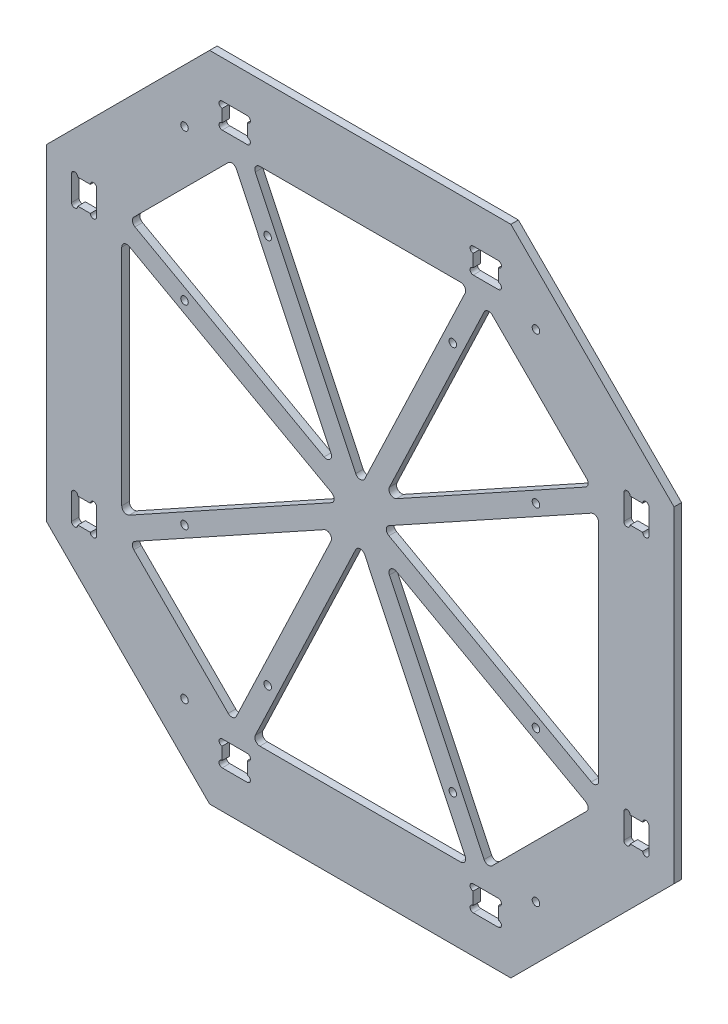
SolidWorks part; units mm, degrees
material "Thornel Mat VMA"
ref_plane "前视基准面" through (0, 0, 0) normal (0, 0, 1) x (1, 0, 0)
ref_plane "上视基准面" through (0, 0, 0) normal (0, 1, 0) x (1, 0, 0)
ref_plane "右视基准面" through (0, 0, 0) normal (1, 0, 0) x (0, 0, -1)
sketch "草图1" plane through (0, 0, 0) normal (0, 0, 1) x (1, 0, 0)
  line L1 (-125, -130) -> (125, -130)
  line L2 (-125, -130) -> (-125, 130)
  line L3 (-125, 130) -> (125, 130)
  line L4 (125, -130) -> (125, 130)
  line L5 (0, 130) -> (0, -130) construction
  line L6 (-125, 0) -> (125, 0) construction
  point P0 (0, 0)
  dimension "D1" = 250
  dimension "D2" = 260
extrude "凸台-拉伸1" add sketch "草图1" along normal mid plane 3
sketch "草图2" plane through (0, 0, -1.5) normal (0, 0, -1) x (-1, 0, 0)
  line L0 (0, 0) -> (125, 0) construction
  line L1 (125, 130) -> (125, -130) construction
  line L2 (55, -105) -> (55, -115)
  line L3 (45, -105) -> (55, -105)
  line L4 (-55, 105) -> (-45, 105)
  line L5 (-45, 105) -> (-45, 115)
  line L6 (-45, 115) -> (-55, 115)
  line L7 (-55, 115) -> (-55, 105)
  line L8 (-55, 105) -> (-45, 105)
  line L9 (-45, 105) -> (-45, 115)
  line L10 (-45, 115) -> (-55, 115)
  line L11 (-55, 115) -> (-55, 105)
  line L12 (55, 115) -> (45, 115)
  line L13 (45, 115) -> (45, 105)
  line L14 (45, 105) -> (55, 105)
  line L15 (55, 105) -> (55, 115)
  line L16 (55, 115) -> (45, 115)
  line L17 (45, 115) -> (45, 105)
  line L18 (45, 105) -> (55, 105)
  line L19 (55, 105) -> (55, 115)
  line L20 (105, 60) -> (105, 50)
  line L21 (105, 50) -> (115, 50)
  line L22 (115, 50) -> (115, 60)
  line L23 (115, 60) -> (105, 60)
  line L24 (105, 60) -> (105, 50)
  line L25 (105, 50) -> (115, 50)
  line L26 (115, 50) -> (115, 60)
  line L27 (115, 60) -> (105, 60)
  line L28 (115, -60) -> (115, -50)
  line L29 (115, -50) -> (105, -50)
  line L30 (105, -50) -> (105, -60)
  line L31 (105, -60) -> (115, -60)
  line L32 (115, -60) -> (115, -50)
  line L33 (115, -50) -> (105, -50)
  line L34 (105, -50) -> (105, -60)
  line L35 (105, -60) -> (115, -60)
  line L36 (45, -115) -> (45, -105)
  line L37 (55, -115) -> (45, -115)
  line L38 (-55, -115) -> (-55, -105)
  line L39 (-45, -115) -> (-55, -115)
  line L40 (-45, -105) -> (-45, -115)
  line L41 (-55, -105) -> (-45, -105)
  line L42 (0, 0) -> (0, 130) construction
  line L43 (-125, 130) -> (125, 130) construction
  line L44 (-115, 60) -> (-105, 60)
  line L45 (-115, 50) -> (-115, 60)
  line L46 (-105, 50) -> (-115, 50)
  line L47 (-105, 60) -> (-105, 50)
  line L48 (-105, -60) -> (-115, -60)
  line L49 (-105, -50) -> (-105, -60)
  line L50 (-115, -50) -> (-105, -50)
  line L51 (-115, -60) -> (-115, -50)
  dimension "D1" = 0
  dimension "D2" = 0
  dimension "D3" = 0
  dimension "D4" = 0
extrude "切除-拉伸1" cut sketch "草图2" against normal mid plane 10
sketch "草图3" plane through (0, 0, -1.5) normal (0, 0, -1) x (-1, 0, 0)
  line L0 (-55, 115) -> (-55, 105) construction
  line L1 (-45, 105) -> (-45, 115) construction
  line L2 (0, 0) -> (0, 130) construction
  line L3 (-125, 130) -> (125, 130) construction
  circle A0 centre (-55, 113.75) radius 1.25
  circle A1 centre (-55, 106.25) radius 1.25
  circle A2 centre (-45, 106.25) radius 1.25
  circle A3 centre (-45, 113.75) radius 1.25
  circle A4 centre (45, 113.75) radius 1.25
  circle A5 centre (45, 106.25) radius 1.25
  circle A6 centre (55, 106.25) radius 1.25
  circle A7 centre (55, 113.75) radius 1.25
  dimension "D1" = 2.5
extrude "切除-拉伸2" cut sketch "草图3" against normal mid plane 10
sketch "草图4" plane through (0, 0, -1.5) normal (0, 0, -1) x (-1, 0, 0)
  line L0 (115, 60) -> (105, 60) construction
  line L1 (105, 50) -> (115, 50) construction
  line L2 (105, 60) -> (105, 50) construction
  line L3 (0, 0) -> (125, 0) construction
  line L4 (125, 130) -> (125, -130) construction
  circle A0 centre (106.25, 60) radius 1.25
  circle A1 centre (113.75, 60) radius 1.25
  circle A2 centre (106.25, 50) radius 1.25
  circle A3 centre (113.75, 50) radius 1.25
  circle A4 centre (113.75, -50) radius 1.25
  circle A5 centre (106.25, -50) radius 1.25
  circle A6 centre (113.75, -60) radius 1.25
  circle A7 centre (106.25, -60) radius 1.25
  dimension "D1" = 2.5
extrude "切除-拉伸3" cut sketch "草图4" against normal mid plane 10
mirror "镜向1" about plane through (0, 0, 0) normal (1, 0, 0) of "切除-拉伸3"
mirror "镜向2" about plane through (0, 0, 0) normal (0, 1, 0) of "切除-拉伸2"
sketch "草图5" plane through (0, 0, -1.5) normal (0, 0, -1) x (-1, 0, 0)
  line L0 (-60, 130) -> (-125, 65)
  line L1 (-125, 130) -> (125, 130) construction
  line L2 (-125, -130) -> (-125, 130) construction
  line L3 (-55, 112.5) -> (-55, 107.5) construction
  line L4 (-107.5, 60) -> (-112.5, 60) construction
  line L5 (0, 0) -> (125, 0) construction
  line L6 (125, 130) -> (125, -130) construction
  line L7 (-125, 65) -> (-125, 130)
  line L8 (-125, 130) -> (-60, 130)
  line L9 (-125, -130) -> (-60, -130)
  line L10 (-125, -65) -> (-125, -130)
  line L11 (-60, -130) -> (-125, -65)
  dimension "D1" = 5
  dimension "D2" = 5
extrude "切除-拉伸4" cut sketch "草图5" against normal mid plane 10
mirror "镜向3" about plane through (0, 0, 0) normal (1, 0, 0) of "切除-拉伸4"
sketch "草图6" plane through (0, 0, -1.5) normal (0, 0, -1) x (-1, 0, 0)
  line L16 (95, -52.5736) -> (95, 52.5736)
  line L17 (95, 52.5736) -> (47.5736, 100)
  line L18 (47.5736, 100) -> (-47.5736, 100)
  line L19 (-47.5736, 100) -> (-95, 52.5736)
  line L20 (-95, 52.5736) -> (-95, -52.5736)
  line L21 (-95, -52.5736) -> (-47.5736, -100)
  line L22 (-47.5736, -100) -> (47.5736, -100)
  line L23 (47.5736, -100) -> (95, -52.5736)
  line L24 (95, -52.5736) -> (95, 52.5736)
  line L25 (95, 52.5736) -> (47.5736, 100)
  line L26 (47.5736, 100) -> (-47.5736, 100)
  line L27 (-47.5736, 100) -> (-95, 52.5736)
  line L28 (-95, 52.5736) -> (-95, -52.5736)
  line L29 (-95, -52.5736) -> (-47.5736, -100)
  line L30 (-47.5736, -100) -> (47.5736, -100)
  line L31 (47.5736, -100) -> (95, -52.5736)
  dimension "D1" = 30
extrude "切除-拉伸5" cut sketch "草图6" against normal mid plane 10
sketch "草图7" plane through (0, 0, -1.5) normal (0, 0, -1) x (-1, 0, 0)
  line L0 (-47.5736, 100) -> (47.5736, -100) construction
  line L1 (47.5736, 100) -> (-47.5736, -100) construction
  line L2 (-95, 52.5736) -> (0, 0) construction
  line L3 (-95, -52.5736) -> (95, 52.5736) construction
  line L4 (-51.1857, 98.2816) -> (-8.9647, 9.5328)
  line L5 (43.9615, 101.7184) -> (0, 9.311)
  line L6 (-96.9368, 49.0738) -> (-8.261, 0)
  line L7 (-93.0632, -56.0734) -> (-8.9647, -9.5328)
  line L8 (-43.9615, 101.7184) -> (0, 9.311)
  line L9 (51.1857, 98.2816) -> (8.9647, 9.5328)
  line L10 (-93.0632, 56.0734) -> (-8.9647, 9.5328)
  line L11 (-96.9368, -49.0738) -> (-8.261, 0)
  line L12 (-51.1857, 98.2816) -> (-43.9615, 101.7184)
  line L13 (43.9615, -101.7184) -> (51.1857, -98.2816)
  line L14 (43.9615, 101.7184) -> (51.1857, 98.2816)
  line L15 (-51.1857, -98.2816) -> (-43.9615, -101.7184)
  line L16 (-96.9368, 49.0738) -> (-93.0632, 56.0734)
  line L17 (93.0632, -56.0734) -> (96.9368, -49.0738)
  line L18 (-93.0632, -56.0734) -> (-96.9368, -49.0738)
  line L19 (96.9368, 49.0738) -> (93.0632, 56.0734)
  line L21 (-93.0632, -56.0734) -> (96.9368, 49.0738) construction
  line L22 (-8.9647, -9.5328) -> (-51.1857, -98.2816)
  line L23 (43.9615, 101.7184) -> (-51.1857, -98.2816) construction
  line L24 (0, -9.311) -> (43.9615, -101.7184)
  line L25 (-51.1857, 98.2816) -> (43.9615, -101.7184) construction
  line L27 (-96.9368, 49.0738) -> (93.0632, -56.0734) construction
  line L29 (-96.9368, -49.0738) -> (93.0632, 56.0734) construction
  line L32 (-93.0632, 56.0734) -> (96.9368, -49.0738) construction
  line L35 (-43.9615, 101.7184) -> (51.1857, -98.2816) construction
  line L36 (8.9647, 9.5328) -> (93.0632, 56.0734)
  line L38 (51.1857, 98.2816) -> (-43.9615, -101.7184) construction
  line L39 (8.261, 0) -> (96.9368, -49.0738)
  line L41 (8.9647, -9.5328) -> (51.1857, -98.2816)
  line L42 (0, 0) -> (95, -52.5736) construction
  line L43 (-95, 52.5736) -> (95, -52.5736) construction
  line L45 (8.261, 0) -> (96.9368, 49.0738)
  line L46 (0, -9.311) -> (-43.9615, -101.7184)
  line L47 (8.9647, -9.5328) -> (93.0632, -56.0734)
  dimension "D1" = 4
  dimension "D2" = 4
extrude "凸台-拉伸2" add sketch "草图7" against normal up to surface (3 mm away) up to face at (0, 0, 1.5)
sketch "草图8" [suppressed] plane through (0, 0, 1.5) normal (0, 0, 1) x (1, 0, 0)
  line L0 (55, 105) -> (45, 105) construction
  line L1 (-105, -105) -> (105, -105)
  line L2 (-105, -105) -> (-105, 105)
  line L3 (-105, 105) -> (105, 105)
  line L4 (105, -105) -> (105, 105)
  line L5 (0, 105) -> (0, -105) construction
  line L6 (-105, 0) -> (105, 0) construction
  line L7 (105, 50) -> (105, 60) construction
  point P0 (0, 0)
extrude "切除-拉伸6" [suppressed] cut sketch "草图8" against normal blind 10
sketch "草图9" plane through (0, 0, -1.5) normal (0, 0, -1) x (-1, 0, 0)
  line L4 (85, 295) -> (55, 295)
  line L5 (55, 295) -> (55, -295)
  line L6 (55, -295) -> (85, -295)
  line L7 (85, -295) -> (85, 295)
  line L8 (85, 295) -> (55, 295) construction
  line L9 (55, 295) -> (55, -295) construction
  line L10 (55, -295) -> (85, -295) construction
  line L11 (85, -295) -> (85, 295) construction
  line L60 (55, 30.4373) -> (85, 47.0395) construction
  line L61 (8.261, 0) -> (95, 48.0019) construction
  line L63 (92.057, 55.5166) -> (8.9647, 9.5328) construction
  line L64 (70, 38.7384) -> (70, 98.7384) construction
  line L65 (0, 0) -> (125, 0) construction
  line L66 (125, 65) -> (125, -65) construction
  line L67 (70, -38.7384) -> (70, -98.7384) construction
  line L68 (55, -30.4373) -> (85, -47.0395) construction
  circle A0 centre (70, 38.7384) radius 1.5
  circle A1 centre (70, 98.7384) radius 1.5
  circle A2 centre (70, -98.7384) radius 1.5
  circle A3 centre (70, -38.7384) radius 1.5
  dimension "D3" = 3
  dimension "D2" = 4
  dimension "D4" = 60
  dimension "D1" = 0
extrude "切除-拉伸7" cut sketch "草图9" against normal blind 10
mirror "镜向4" about plane through (0, 0, 0) normal (1, 0, 0) of "切除-拉伸7"
fillet "圆角1" radius 2 24 edges at (8.261, 0, 0) (95, -48.0019, 0) (95, 48.0019, 0) (8.9647, 9.5328, 0) (92.057, 55.5166, 0) (50.5752, 96.9984, 0) (0, 9.311, 0) (43.144, 100, 0) (-43.144, 100, 0) (-8.9647, 9.5328, 0) (-50.5752, 96.9984, 0) (-92.057, 55.5166, 0) (-8.261, 0, 0) (-95, 48.0019, 0) (-95, -48.0019, 0) (-8.9647, -9.5328, 0) (-92.057, -55.5166, 0) (-50.5752, -96.9984, 0) (0, -9.311, 0) (-43.144, -100, 0) (43.144, -100, 0) (8.9647, -9.5328, 0) (92.057, -55.5166, 0) (50.5752, -96.9984, 0)
sketch "草图10" plane through (0, 0, -1.5) normal (0, 0, -1) x (-1, 0, 0)
  line L0 (-41.7838, -97.1408) -> (-49.0079, -93.704) construction
  line L1 (-36.8695, -77.5) -> (36.8695, -77.5) construction
  line L2 (-36.8695, -77.5) -> (-36.8695, 77.5) construction
  line L3 (-36.8695, 77.5) -> (36.8695, 77.5) construction
  line L4 (36.8695, -77.5) -> (36.8695, 77.5) construction
  line L5 (0, 77.5) -> (0, -77.5) construction
  line L6 (-36.8695, 0) -> (36.8695, 0) construction
  line L7 (-41.7838, -97.1408) -> (-1.806, -13.1073) construction
  line L8 (-11.641, -15.1583) -> (-49.3582, -94.4402) construction
  line L9 (-45.3959, -95.4224) -> (44.5639, 93.6735) construction
  line L10 (11.641, 15.1583) -> (49.3582, 94.4402) construction
  circle A0 centre (36.8695, 77.5) radius 1.5
  circle A1 centre (-36.8695, 77.5) radius 1.5
  circle A2 centre (-36.8695, -77.5) radius 1.5
  circle A3 centre (36.8695, -77.5) radius 1.5
  point P0 (0, 0)
  dimension "D2" = 3
  dimension "D1" = 155
extrude "切除-拉伸8" cut sketch "草图10" against normal blind 10
sketch "草图11" [suppressed] plane through (0, 0, -1.5) normal (0, 0, -1) x (-1, 0, 0)
  line L0 (-125, -122.5) -> (125, -122.5) construction
  line L1 (-125, -130) -> (-125, 130) construction
  line L2 (125, 130) -> (125, -130) construction
  line L3 (125, -130) -> (-125, -130) construction
  line L4 (0, -122.5) -> (0, -130) construction
  circle A0 centre (-100, -122.5) radius 1.525
  circle A1 centre (100, -122.5) radius 1.525
  circle A2 centre (0, -122.5) radius 1.525
  dimension "D2" = 3.05
  dimension "D1" = 7.5
  dimension "D3" = 100
extrude "切除-拉伸9" [suppressed] cut sketch "草图11" against normal blind 10
mirror "镜向5" [suppressed] about plane through (0, 0, 0) normal (0, 1, 0)
sketch "草图12" [suppressed] plane through (0, 0, -1.5) normal (0, 0, -1) x (-1, 0, 0)
  line L1 (-90, -90) -> (90, -90)
  line L2 (-90, -90) -> (-90, 90)
  line L3 (-90, 90) -> (90, 90)
  line L4 (90, -90) -> (90, 90)
  line L5 (0, 90) -> (0, -90) construction
  line L6 (-90, 0) -> (90, 0) construction
  point P0 (0, 0)
  dimension "D1" = 180
extrude "切除-拉伸10" [suppressed] cut sketch "草图12" against normal blind 10
fillet "圆角2" [suppressed] radius 5
sketch "草图13" [suppressed] plane through (0, 0, -1.5) normal (0, 0, -1) x (-1, 0, 0)
  line L0 (-55, 107.5) -> (-55, 105)
  line L1 (-45, 107.5) -> (-45, 105)
  line L2 (45, 107.5) -> (45, 105)
  line L3 (55, 107.5) -> (55, 105)
  line L4 (-107.5, 60) -> (-105, 60)
  line L5 (-107.5, 50) -> (-105, 50)
  line L6 (-107.5, -50) -> (-105, -50)
  line L7 (-107.5, -60) -> (-105, -60)
  line L8 (55, -107.5) -> (55, -105)
  line L9 (0, 0) -> (203.8061, 0) construction
  line L10 (45, -107.5) -> (45, -105)
  line L11 (-45, -107.5) -> (-45, -105)
  line L12 (-55, -107.5) -> (-55, -105)
  line L13 (0, 105) -> (0, 0) construction
  line L14 (45, 105) -> (-45, 105) construction
  line L15 (107.5, -60) -> (105, -60)
  line L16 (107.5, -50) -> (105, -50)
  line L17 (107.5, 50) -> (105, 50)
  line L18 (107.5, 60) -> (105, 60)
  arc A0 (-55, 107.5) -> (-55, 105) centre (-55, 106.25) ccw construction
  arc A1 (-55, 107.5) -> (-55, 105) centre (-55, 106.25) ccw
  arc A2 (-45, 105) -> (-45, 107.5) centre (-45, 106.25) ccw construction
  arc A3 (-45, 105) -> (-45, 107.5) centre (-45, 106.25) ccw
  arc A4 (45, 107.5) -> (45, 105) centre (45, 106.25) ccw construction
  arc A5 (45, 107.5) -> (45, 105) centre (45, 106.25) ccw
  arc A6 (55, 105) -> (55, 107.5) centre (55, 106.25) ccw construction
  arc A7 (55, 105) -> (55, 107.5) centre (55, 106.25) ccw
  arc A8 (-105, 60) -> (-107.5, 60) centre (-106.25, 60) ccw construction
  arc A9 (-107.5, 50) -> (-105, 50) centre (-106.25, 50) ccw construction
  arc A10 (-105, -50) -> (-107.5, -50) centre (-106.25, -50) ccw construction
  arc A11 (-107.5, -60) -> (-105, -60) centre (-106.25, -60) ccw construction
  arc A12 (-105, 60) -> (-107.5, 60) centre (-106.25, 60) ccw
  arc A13 (-107.5, 50) -> (-105, 50) centre (-106.25, 50) ccw
  arc A14 (-105, -50) -> (-107.5, -50) centre (-106.25, -50) ccw
  arc A15 (-107.5, -60) -> (-105, -60) centre (-106.25, -60) ccw
  arc A16 (55, -105) -> (55, -107.5) centre (55, -106.25) cw
  arc A17 (45, -107.5) -> (45, -105) centre (45, -106.25) cw
  arc A18 (-45, -105) -> (-45, -107.5) centre (-45, -106.25) cw
  arc A19 (-55, -107.5) -> (-55, -105) centre (-55, -106.25) cw
  arc A20 (107.5, -60) -> (105, -60) centre (106.25, -60) cw
  arc A21 (105, -50) -> (107.5, -50) centre (106.25, -50) cw
  arc A22 (107.5, 50) -> (105, 50) centre (106.25, 50) cw
  arc A23 (105, 60) -> (107.5, 60) centre (106.25, 60) cw
extrude "凸台-拉伸3" [suppressed] add sketch "草图13" against normal up to surface (3 mm away)
sketch "草图14" [suppressed] plane through (0, 0, 1.5) normal (0, 0, 1) x (1, 0, 0)
  line L0 (85, -117) -> (85, -115) construction
  line L1 (85, -115) -> (65, -115) construction
  line L2 (65, -115) -> (65, -117) construction
  line L3 (65, -117) -> (85, -117) construction
  line L4 (15, -115) -> (15, -117) construction
  line L5 (15, -117) -> (35, -117) construction
  line L6 (35, -117) -> (35, -115) construction
  line L7 (35, -115) -> (15, -115) construction
  line L8 (-15, -117) -> (-15, -115) construction
  line L9 (-15, -115) -> (-35, -115) construction
  line L10 (-35, -115) -> (-35, -117) construction
  line L11 (-35, -117) -> (-15, -117) construction
  line L12 (-65, -115) -> (-85, -115) construction
  line L13 (-85, -115) -> (-85, -117) construction
  line L14 (-85, -117) -> (-65, -117) construction
  line L15 (-65, -117) -> (-65, -115) construction
  line L16 (85, -117) -> (85, -115) construction
  line L17 (85, -115) -> (65, -115) construction
  line L18 (65, -115) -> (65, -117) construction
  line L19 (65, -117) -> (85, -117) construction
  line L20 (15, -115) -> (15, -117) construction
  line L21 (15, -117) -> (35, -117) construction
  line L22 (35, -117) -> (35, -115) construction
  line L23 (35, -115) -> (15, -115) construction
  line L24 (-15, -117) -> (-15, -115) construction
  line L25 (-15, -115) -> (-35, -115) construction
  line L26 (-35, -115) -> (-35, -117) construction
  line L27 (-35, -117) -> (-15, -117) construction
  line L28 (-65, -115) -> (-85, -115) construction
  line L29 (-85, -115) -> (-85, -117) construction
  line L30 (-85, -117) -> (-65, -117) construction
  line L31 (-65, -117) -> (-65, -115) construction
  line L32 (85.05, -117.05) -> (85.05, -114.95)
  line L33 (85.05, -114.95) -> (64.95, -114.95)
  line L34 (64.95, -114.95) -> (64.95, -117.05)
  line L35 (64.95, -117.05) -> (85.05, -117.05)
  line L36 (14.95, -114.95) -> (14.95, -117.05)
  line L37 (14.95, -117.05) -> (35.05, -117.05)
  line L38 (35.05, -117.05) -> (35.05, -114.95)
  line L39 (35.05, -114.95) -> (14.95, -114.95)
  line L40 (-14.95, -117.05) -> (-14.95, -114.95)
  line L41 (-14.95, -114.95) -> (-35.05, -114.95)
  line L42 (-35.05, -114.95) -> (-35.05, -117.05)
  line L43 (-35.05, -117.05) -> (-14.95, -117.05)
  line L44 (-64.95, -114.95) -> (-85.05, -114.95)
  line L45 (-85.05, -114.95) -> (-85.05, -117.05)
  line L46 (-85.05, -117.05) -> (-64.95, -117.05)
  line L47 (-64.95, -117.05) -> (-64.95, -114.95)
  dimension "D1" = 0.05
sketch "草图15" [suppressed] plane through (0, 0, 1.5) normal (0, 0, 1) x (1, 0, 0)
  line L0 (117, 70) -> (117, 90) construction
  line L1 (117, 90) -> (115, 90) construction
  line L2 (115, 90) -> (115, 70) construction
  line L3 (115, 70) -> (117, 70) construction
  line L4 (115, 20) -> (117, 20) construction
  line L5 (117, 20) -> (117, 40) construction
  line L6 (117, 40) -> (115, 40) construction
  line L7 (115, 40) -> (115, 20) construction
  line L8 (117, -20) -> (115, -20) construction
  line L9 (115, -20) -> (115, -40) construction
  line L10 (115, -40) -> (117, -40) construction
  line L11 (117, -40) -> (117, -20) construction
  line L12 (117, -90) -> (117, -70) construction
  line L13 (117, -70) -> (115, -70) construction
  line L14 (115, -70) -> (115, -90) construction
  line L15 (115, -90) -> (117, -90) construction
  line L16 (117, 70) -> (117, 90) construction
  line L17 (117, 90) -> (115, 90) construction
  line L18 (115, 90) -> (115, 70) construction
  line L19 (115, 70) -> (117, 70) construction
  line L20 (115, 20) -> (117, 20) construction
  line L21 (117, 20) -> (117, 40) construction
  line L22 (117, 40) -> (115, 40) construction
  line L23 (115, 40) -> (115, 20) construction
  line L24 (117, -20) -> (115, -20) construction
  line L25 (115, -20) -> (115, -40) construction
  line L26 (115, -40) -> (117, -40) construction
  line L27 (117, -40) -> (117, -20) construction
  line L28 (117, -90) -> (117, -70) construction
  line L29 (117, -70) -> (115, -70) construction
  line L30 (115, -70) -> (115, -90) construction
  line L31 (115, -90) -> (117, -90) construction
  line L32 (117.05, 69.95) -> (117.05, 90.05)
  line L33 (117.05, 90.05) -> (114.95, 90.05)
  line L34 (114.95, 90.05) -> (114.95, 69.95)
  line L35 (114.95, 69.95) -> (117.05, 69.95)
  line L36 (114.95, 19.95) -> (117.05, 19.95)
  line L37 (117.05, 19.95) -> (117.05, 40.05)
  line L38 (117.05, 40.05) -> (114.95, 40.05)
  line L39 (114.95, 40.05) -> (114.95, 19.95)
  line L40 (117.05, -19.95) -> (114.95, -19.95)
  line L41 (114.95, -19.95) -> (114.95, -40.05)
  line L42 (114.95, -40.05) -> (117.05, -40.05)
  line L43 (117.05, -40.05) -> (117.05, -19.95)
  line L44 (117.05, -90.05) -> (117.05, -69.95)
  line L45 (117.05, -69.95) -> (114.95, -69.95)
  line L46 (114.95, -69.95) -> (114.95, -90.05)
  line L47 (114.95, -90.05) -> (117.05, -90.05)
  dimension "D1" = 0.05
extrude "切除-拉伸12" [suppressed] cut sketch "草图14" against normal up to surface (3 mm away)
mirror "镜向6" [suppressed] about plane through (0, 0, 0) normal (0, 1, 0)
extrude "切除-拉伸13" [suppressed] cut sketch "草图15" against normal up to surface (3 mm away)
mirror "镜向7" [suppressed] about plane through (0, 0, 0) normal (1, 0, 0)
sketch "草图16" [suppressed] plane through (0, 0, -1.5) normal (0, 0, -1) x (-1, 0, 0)
  line L0 (-64.95, -117.05) -> (-85.05, -117.05) construction
  line L1 (-85.05, -114.95) -> (-64.95, -114.95) construction
  line L2 (-35.05, -114.95) -> (-14.95, -114.95) construction
  line L3 (-14.95, -117.05) -> (-35.05, -117.05) construction
  line L4 (14.95, -114.95) -> (35.05, -114.95) construction
  line L5 (35.05, -117.05) -> (14.95, -117.05) construction
  line L6 (64.95, -114.95) -> (85.05, -114.95) construction
  line L7 (85.05, -117.05) -> (64.95, -117.05) construction
  arc A0 (-84.2779, -116) -> (-83.6221, -116) centre (-83.95, -117.05) ccw
  arc A1 (-83.6221, -116) -> (-84.2779, -116) centre (-83.95, -114.95) ccw
  arc A2 (-65.7221, -116) -> (-66.3779, -116) centre (-66.05, -114.95) ccw
  arc A3 (-66.3779, -116) -> (-65.7221, -116) centre (-66.05, -117.05) ccw
  arc A4 (-33.6221, -116) -> (-34.2779, -116) centre (-33.95, -114.95) ccw
  arc A5 (-34.2779, -116) -> (-33.6221, -116) centre (-33.95, -117.05) ccw
  arc A6 (-16.3779, -116) -> (-15.7221, -116) centre (-16.05, -117.05) ccw
  arc A7 (-15.7221, -116) -> (-16.3779, -116) centre (-16.05, -114.95) ccw
  arc A8 (16.3779, -116) -> (15.7221, -116) centre (16.05, -114.95) ccw
  arc A9 (15.7221, -116) -> (16.3779, -116) centre (16.05, -117.05) ccw
  arc A10 (34.2779, -116) -> (33.6221, -116) centre (33.95, -114.95) ccw
  arc A11 (33.6221, -116) -> (34.2779, -116) centre (33.95, -117.05) ccw
  arc A12 (66.3779, -116) -> (65.7221, -116) centre (66.05, -114.95) ccw
  arc A13 (65.7221, -116) -> (66.3779, -116) centre (66.05, -117.05) ccw
  arc A14 (84.2779, -116) -> (83.6221, -116) centre (83.95, -114.95) ccw
  arc A15 (83.6221, -116) -> (84.2779, -116) centre (83.95, -117.05) ccw
  dimension "D1" = 2.2
  dimension "D2" = 2.2
extrude "切除-拉伸14" [suppressed] cut sketch "草图16" against normal up to surface (3 mm away)
mirror "镜向8" [suppressed] about plane through (0, 0, 0) normal (0, 1, 0)
sketch "草图17" [suppressed] plane through (0, 0, -1.5) normal (0, 0, -1) x (-1, 0, 0)
  line L0 (-117.05, -90.05) -> (-117.05, -69.95) construction
  line L1 (-114.95, -69.95) -> (-114.95, -90.05) construction
  line L2 (-117.05, -40.05) -> (-117.05, -19.95) construction
  line L3 (-114.95, -19.95) -> (-114.95, -40.05) construction
  line L4 (0, 0) -> (-140.9503, 0) construction
  arc A0 (-116, -88.6221) -> (-116, -89.2779) centre (-117.05, -88.95) ccw
  arc A1 (-116, -89.2779) -> (-116, -88.6221) centre (-114.95, -88.95) ccw
  arc A2 (-116, -70.7221) -> (-116, -71.3779) centre (-117.05, -71.05) ccw
  arc A3 (-116, -71.3779) -> (-116, -70.7221) centre (-114.95, -71.05) ccw
  arc A4 (-116, -38.6221) -> (-116, -39.2779) centre (-117.05, -38.95) ccw
  arc A5 (-116, -39.2779) -> (-116, -38.6221) centre (-114.95, -38.95) ccw
  arc A6 (-116, -20.7221) -> (-116, -21.3779) centre (-117.05, -21.05) ccw
  arc A7 (-116, -21.3779) -> (-116, -20.7221) centre (-114.95, -21.05) ccw
  arc A8 (-116, 21.3779) -> (-116, 20.7221) centre (-114.95, 21.05) cw
  arc A9 (-116, 20.7221) -> (-116, 21.3779) centre (-117.05, 21.05) cw
  arc A10 (-116, 39.2779) -> (-116, 38.6221) centre (-114.95, 38.95) cw
  arc A11 (-116, 38.6221) -> (-116, 39.2779) centre (-117.05, 38.95) cw
  arc A12 (-116, 71.3779) -> (-116, 70.7221) centre (-114.95, 71.05) cw
  arc A13 (-116, 70.7221) -> (-116, 71.3779) centre (-117.05, 71.05) cw
  arc A14 (-116, 89.2779) -> (-116, 88.6221) centre (-114.95, 88.95) cw
  arc A15 (-116, 88.6221) -> (-116, 89.2779) centre (-117.05, 88.95) cw
  dimension "D1" = 2.2
extrude "切除-拉伸15" [suppressed] cut sketch "草图17" against normal blind 40
mirror "镜向9" [suppressed] about plane through (0, 0, 0) normal (1, 0, 0)
sketch "草图18" [suppressed] plane through (0, 0, -1.5) normal (0, 0, -1) x (-1, 0, 0)
  line L0 (-35, 115) -> (-15, 115) construction
  line L1 (-15, 115) -> (-15, 117) construction
  line L2 (-15, 117) -> (-35, 117) construction
  line L3 (-35, 117) -> (-35, 115) construction
  line L4 (-65, 115) -> (-65, 117) construction
  line L5 (-65, 117) -> (-85, 117) construction
  line L6 (-85, 117) -> (-85, 115) construction
  line L7 (-85, 115) -> (-65, 115) construction
  line L8 (35, 117) -> (15, 117) construction
  line L9 (15, 117) -> (15, 115) construction
  line L10 (15, 115) -> (35, 115) construction
  line L11 (35, 115) -> (35, 117) construction
  line L12 (85, 117) -> (65, 117) construction
  line L13 (65, 117) -> (65, 115) construction
  line L14 (65, 115) -> (85, 115) construction
  line L15 (85, 115) -> (85, 117) construction
  line L16 (-35, 115) -> (-15, 115) construction
  line L17 (-15, 115) -> (-15, 117) construction
  line L18 (-15, 117) -> (-35, 117) construction
  line L19 (-35, 117) -> (-35, 115) construction
  line L20 (-65, 115) -> (-65, 117) construction
  line L21 (-65, 117) -> (-85, 117) construction
  line L22 (-85, 117) -> (-85, 115) construction
  line L23 (-85, 115) -> (-65, 115) construction
  line L24 (35, 117) -> (15, 117) construction
  line L25 (15, 117) -> (15, 115) construction
  line L26 (15, 115) -> (35, 115) construction
  line L27 (35, 115) -> (35, 117) construction
  line L28 (85, 117) -> (65, 117) construction
  line L29 (65, 117) -> (65, 115) construction
  line L30 (65, 115) -> (85, 115) construction
  line L31 (85, 115) -> (85, 117) construction
  line L32 (117, -70) -> (115, -70) construction
  line L33 (115, -70) -> (115, -90) construction
  line L34 (115, -90) -> (117, -90) construction
  line L35 (117, -90) -> (117, -70) construction
  line L36 (117, -40) -> (117, -20) construction
  line L37 (117, -20) -> (115, -20) construction
  line L38 (115, -20) -> (115, -40) construction
  line L39 (115, -40) -> (117, -40) construction
  line L40 (115, 40) -> (115, 20) construction
  line L41 (115, 20) -> (117, 20) construction
  line L42 (117, 20) -> (117, 40) construction
  line L43 (117, 40) -> (115, 40) construction
  line L44 (117, 90) -> (115, 90) construction
  line L45 (115, 90) -> (115, 70) construction
  line L46 (115, 70) -> (117, 70) construction
  line L47 (117, 70) -> (117, 90) construction
  line L48 (117, -70) -> (115, -70) construction
  line L49 (115, -70) -> (115, -90) construction
  line L50 (115, -90) -> (117, -90) construction
  line L51 (117, -90) -> (117, -70) construction
  line L52 (117, -40) -> (117, -20) construction
  line L53 (117, -20) -> (115, -20) construction
  line L54 (115, -20) -> (115, -40) construction
  line L55 (115, -40) -> (117, -40) construction
  line L56 (115, 40) -> (115, 20) construction
  line L57 (115, 20) -> (117, 20) construction
  line L58 (117, 20) -> (117, 40) construction
  line L59 (117, 40) -> (115, 40) construction
  line L60 (117, 90) -> (115, 90) construction
  line L61 (115, 90) -> (115, 70) construction
  line L62 (115, 70) -> (117, 70) construction
  line L63 (117, 70) -> (117, 90) construction
  line L64 (-35.05, 114.95) -> (-14.95, 114.95)
  line L65 (-14.95, 114.95) -> (-14.95, 117.05)
  line L66 (-14.95, 117.05) -> (-35.05, 117.05)
  line L67 (-35.05, 117.05) -> (-35.05, 114.95)
  line L68 (-64.95, 114.95) -> (-64.95, 117.05)
  line L69 (-64.95, 117.05) -> (-85.05, 117.05)
  line L70 (-85.05, 117.05) -> (-85.05, 114.95)
  line L71 (-85.05, 114.95) -> (-64.95, 114.95)
  line L72 (35.05, 117.05) -> (14.95, 117.05)
  line L73 (14.95, 117.05) -> (14.95, 114.95)
  line L74 (14.95, 114.95) -> (35.05, 114.95)
  line L75 (35.05, 114.95) -> (35.05, 117.05)
  line L76 (85.05, 117.05) -> (64.95, 117.05)
  line L77 (64.95, 117.05) -> (64.95, 114.95)
  line L78 (64.95, 114.95) -> (85.05, 114.95)
  line L79 (85.05, 114.95) -> (85.05, 117.05)
  line L80 (117.05, -69.95) -> (114.95, -69.95)
  line L81 (114.95, -69.95) -> (114.95, -90.05)
  line L82 (114.95, -90.05) -> (117.05, -90.05)
  line L83 (117.05, -90.05) -> (117.05, -69.95)
  line L84 (117.05, -40.05) -> (117.05, -19.95)
  line L85 (117.05, -19.95) -> (114.95, -19.95)
  line L86 (114.95, -19.95) -> (114.95, -40.05)
  line L87 (114.95, -40.05) -> (117.05, -40.05)
  line L88 (114.95, 40.05) -> (114.95, 19.95)
  line L89 (114.95, 19.95) -> (117.05, 19.95)
  line L90 (117.05, 19.95) -> (117.05, 40.05)
  line L91 (117.05, 40.05) -> (114.95, 40.05)
  line L92 (117.05, 90.05) -> (114.95, 90.05)
  line L93 (114.95, 90.05) -> (114.95, 69.95)
  line L94 (114.95, 69.95) -> (117.05, 69.95)
  line L95 (117.05, 69.95) -> (117.05, 90.05)
  line L96 (0, 0) -> (0, 90.05) construction
  line L97 (-117, 70) -> (-117, 90) construction
  line L98 (-115, 70) -> (-117, 70) construction
  line L99 (-115, 90) -> (-115, 70) construction
  line L100 (-117, 90) -> (-115, 90) construction
  line L101 (-117, 40) -> (-115, 40) construction
  line L102 (-117, 20) -> (-117, 40) construction
  line L103 (-115, 20) -> (-117, 20) construction
  line L104 (-115, 40) -> (-115, 20) construction
  line L105 (-115, -40) -> (-117, -40) construction
  line L106 (-115, -20) -> (-115, -40) construction
  line L107 (-117, -20) -> (-115, -20) construction
  line L108 (-117, -40) -> (-117, -20) construction
  line L109 (-117, -90) -> (-117, -70) construction
  line L110 (-115, -90) -> (-117, -90) construction
  line L111 (-115, -70) -> (-115, -90) construction
  line L112 (-117, -70) -> (-115, -70) construction
  line L113 (-117.05, 69.95) -> (-117.05, 90.05)
  line L114 (-114.95, 69.95) -> (-117.05, 69.95)
  line L115 (-114.95, 90.05) -> (-114.95, 69.95)
  line L116 (-117.05, 90.05) -> (-114.95, 90.05)
  line L117 (-117.05, 40.05) -> (-114.95, 40.05)
  line L118 (-117.05, 19.95) -> (-117.05, 40.05)
  line L119 (-114.95, 19.95) -> (-117.05, 19.95)
  line L120 (-114.95, 40.05) -> (-114.95, 19.95)
  line L121 (-114.95, -40.05) -> (-117.05, -40.05)
  line L122 (-114.95, -19.95) -> (-114.95, -40.05)
  line L123 (-117.05, -19.95) -> (-114.95, -19.95)
  line L124 (-117.05, -40.05) -> (-117.05, -19.95)
  line L125 (-117.05, -90.05) -> (-117.05, -69.95)
  line L126 (-114.95, -90.05) -> (-117.05, -90.05)
  line L127 (-114.95, -69.95) -> (-114.95, -90.05)
  line L128 (-117.05, -69.95) -> (-114.95, -69.95)
  line L129 (0, 0) -> (190.7711, 0) construction
  line L130 (85, -115) -> (85, -117) construction
  line L131 (65, -115) -> (85, -115) construction
  line L132 (65, -117) -> (65, -115) construction
  line L133 (85, -117) -> (65, -117) construction
  line L134 (35, -115) -> (35, -117) construction
  line L135 (15, -115) -> (35, -115) construction
  line L136 (15, -117) -> (15, -115) construction
  line L137 (35, -117) -> (15, -117) construction
  line L138 (-85, -115) -> (-65, -115) construction
  line L139 (-85, -117) -> (-85, -115) construction
  line L140 (-65, -117) -> (-85, -117) construction
  line L141 (-65, -115) -> (-65, -117) construction
  line L142 (-35, -117) -> (-35, -115) construction
  line L143 (-15, -117) -> (-35, -117) construction
  line L144 (-15, -115) -> (-15, -117) construction
  line L145 (-35, -115) -> (-15, -115) construction
  line L146 (85.05, -114.95) -> (85.05, -117.05)
  line L147 (64.95, -114.95) -> (85.05, -114.95)
  line L148 (64.95, -117.05) -> (64.95, -114.95)
  line L149 (85.05, -117.05) -> (64.95, -117.05)
  line L150 (35.05, -114.95) -> (35.05, -117.05)
  line L151 (14.95, -114.95) -> (35.05, -114.95)
  line L152 (14.95, -117.05) -> (14.95, -114.95)
  line L153 (35.05, -117.05) -> (14.95, -117.05)
  line L154 (-85.05, -114.95) -> (-64.95, -114.95)
  line L155 (-85.05, -117.05) -> (-85.05, -114.95)
  line L156 (-64.95, -117.05) -> (-85.05, -117.05)
  line L157 (-64.95, -114.95) -> (-64.95, -117.05)
  line L158 (-35.05, -117.05) -> (-35.05, -114.95)
  line L159 (-14.95, -117.05) -> (-35.05, -117.05)
  line L160 (-14.95, -114.95) -> (-14.95, -117.05)
  line L161 (-35.05, -114.95) -> (-14.95, -114.95)
  dimension "D1" = 0.05
  dimension "D2" = 0.05
extrude "切除-拉伸16" [suppressed] cut sketch "草图18" against normal blind 40
sketch "草图19" [suppressed] plane through (0, 0, -1.5) normal (0, 0, -1) x (-1, 0, 0)
  line L0 (-64.95, 117.05) -> (-85.05, 117.05) construction
  line L1 (-85.05, 114.95) -> (-64.95, 114.95) construction
  line L2 (-14.95, 117.05) -> (-35.05, 117.05) construction
  line L3 (-35.05, 114.95) -> (-14.95, 114.95) construction
  line L4 (35.05, 117.05) -> (14.95, 117.05) construction
  line L5 (14.95, 114.95) -> (35.05, 114.95) construction
  line L6 (85.05, 117.05) -> (64.95, 117.05) construction
  line L7 (64.95, 114.95) -> (85.05, 114.95) construction
  arc A0 (-83.6221, 116) -> (-84.2779, 116) centre (-83.95, 117.05) ccw
  arc A1 (-84.2779, 116) -> (-83.6221, 116) centre (-83.95, 114.95) ccw
  arc A2 (-65.7221, 116) -> (-66.3779, 116) centre (-66.05, 117.05) ccw
  arc A3 (-66.3779, 116) -> (-65.7221, 116) centre (-66.05, 114.95) ccw
  arc A4 (-33.6221, 116) -> (-34.2779, 116) centre (-33.95, 117.05) ccw
  arc A5 (-34.2779, 116) -> (-33.6221, 116) centre (-33.95, 114.95) ccw
  arc A6 (-15.7221, 116) -> (-16.3779, 116) centre (-16.05, 117.05) ccw
  arc A7 (-16.3779, 116) -> (-15.7221, 116) centre (-16.05, 114.95) ccw
  arc A8 (16.3779, 116) -> (15.7221, 116) centre (16.05, 117.05) ccw
  arc A9 (15.7221, 116) -> (16.3779, 116) centre (16.05, 114.95) ccw
  arc A10 (34.2779, 116) -> (33.6221, 116) centre (33.95, 117.05) ccw
  arc A11 (33.6221, 116) -> (34.2779, 116) centre (33.95, 114.95) ccw
  arc A12 (66.3779, 116) -> (65.7221, 116) centre (66.05, 117.05) ccw
  arc A13 (65.7221, 116) -> (66.3779, 116) centre (66.05, 114.95) ccw
  arc A14 (84.2779, 116) -> (83.6221, 116) centre (83.95, 117.05) ccw
  arc A15 (83.6221, 116) -> (84.2779, 116) centre (83.95, 114.95) ccw
  dimension "D1" = 2.2
extrude "切除-拉伸17" [suppressed] cut sketch "草图19" against normal blind 40
mirror "镜向10" [suppressed] about plane through (0, 0, 0) normal (0, 1, 0)
sketch "草图20" [suppressed] plane through (0, 0, -1.5) normal (0, 0, -1) x (-1, 0, 0)
  line L0 (-117.05, 90.05) -> (-117.05, 69.95) construction
  line L1 (-114.95, 69.95) -> (-114.95, 90.05) construction
  line L2 (-117.05, 40.05) -> (-117.05, 19.95) construction
  line L3 (-114.95, 19.95) -> (-114.95, 40.05) construction
  line L4 (-117.05, -19.95) -> (-117.05, -40.05) construction
  line L5 (-114.95, -40.05) -> (-114.95, -19.95) construction
  line L6 (-117.05, -69.95) -> (-117.05, -90.05) construction
  line L7 (-114.95, -90.05) -> (-114.95, -69.95) construction
  arc A0 (-116, 89.2779) -> (-116, 88.6221) centre (-117.05, 88.95) ccw
  arc A1 (-116, 88.6221) -> (-116, 89.2779) centre (-114.95, 88.95) ccw
  arc A2 (-116, 71.3779) -> (-116, 70.7221) centre (-117.05, 71.05) ccw
  arc A3 (-116, 70.7221) -> (-116, 71.3779) centre (-114.95, 71.05) ccw
  arc A4 (-116, 39.2779) -> (-116, 38.6221) centre (-117.05, 38.95) ccw
  arc A5 (-116, 38.6221) -> (-116, 39.2779) centre (-114.95, 38.95) ccw
  arc A6 (-116, 21.3779) -> (-116, 20.7221) centre (-117.05, 21.05) ccw
  arc A7 (-116, 20.7221) -> (-116, 21.3779) centre (-114.95, 21.05) ccw
  arc A8 (-116, -20.7221) -> (-116, -21.3779) centre (-117.05, -21.05) ccw
  arc A9 (-116, -21.3779) -> (-116, -20.7221) centre (-114.95, -21.05) ccw
  arc A10 (-116, -38.6221) -> (-116, -39.2779) centre (-117.05, -38.95) ccw
  arc A11 (-116, -39.2779) -> (-116, -38.6221) centre (-114.95, -38.95) ccw
  arc A12 (-116, -70.7221) -> (-116, -71.3779) centre (-117.05, -71.05) ccw
  arc A13 (-116, -71.3779) -> (-116, -70.7221) centre (-114.95, -71.05) ccw
  arc A14 (-116, -88.6221) -> (-116, -89.2779) centre (-117.05, -88.95) ccw
  arc A15 (-116, -89.2779) -> (-116, -88.6221) centre (-114.95, -88.95) ccw
  dimension "D1" = 2.2
extrude "切除-拉伸18" [suppressed] cut sketch "草图20" against normal blind 40
mirror "镜向11" [suppressed] about plane through (0, 0, 0) normal (1, 0, 0)
fillet "圆角3" [suppressed] radius 3
fillet "圆角4" [suppressed] radius 3
fillet "圆角5" [suppressed] radius 3
sketch "草图21" [suppressed] plane through (0, 0, 1.5) normal (0, 0, 1) x (1, 0, 0)
  line L0 (-85, -145) -> (-55, -145)
  line L1 (-122, -130) -> (122, -130) construction
  line L2 (-85, 145) -> (-55, 145)
  line L3 (122, 130) -> (-122, 130) construction
  line L4 (-55, 295) -> (-85, 295)
  line L5 (-85, 295) -> (-85, -295)
  line L6 (-85, -295) -> (-55, -295)
  line L7 (-55, -295) -> (-55, 295)
  line L9 (-85, 145) -> (-85, 130)
  line L11 (-55, -145) -> (-55, -130)
  line L12 (-85, 130) -> (-55, 130)
  line L13 (-85, -130) -> (-55, -130)
  line L14 (-55, 130) -> (-55, 145)
  line L15 (-85, -130) -> (-85, -145)
  dimension "D2" = 15
  dimension "D3" = 15
  dimension "D1" = 0
extrude "凸台-拉伸4" [suppressed] add sketch "草图21" against normal up to surface (3 mm away)
mirror "镜向12" [suppressed] about plane through (0, 0, 0) normal (1, 0, 0)
fillet "圆角6" [suppressed] radius 3
equation "\"D2@草图7\"=\"D1@草图7\""
